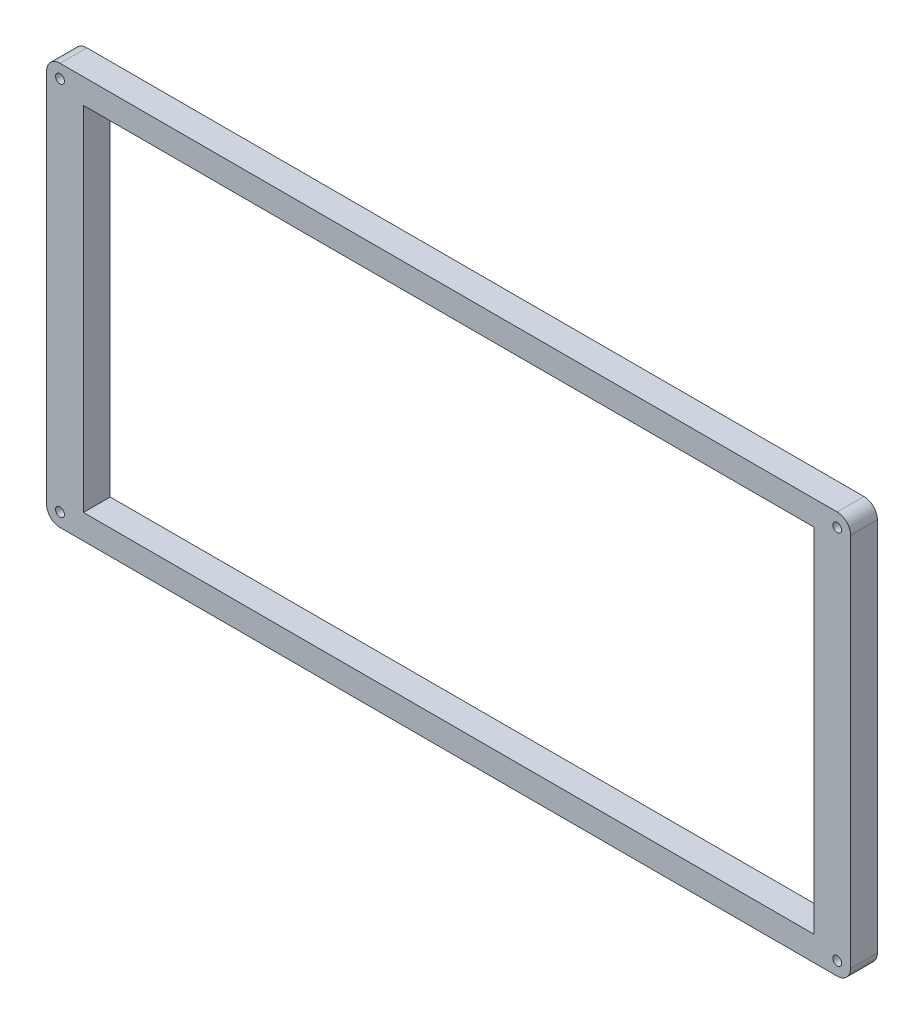
SolidWorks part; units mm, degrees
ref_plane "前视基准面" through (0, 0, 0) normal (0, 0, 1) x (1, 0, 0)
ref_plane "上视基准面" through (0, 0, 0) normal (0, 1, 0) x (1, 0, 0)
ref_plane "右视基准面" through (0, 0, 0) normal (1, 0, 0) x (0, 0, -1)
sketch "草图1" plane through (0, 0, 0) normal (0, 0, 1) x (1, 0, 0)
  line L1 (-77.1552, 109.8741) -> (212.8448, 109.8741)
  line L2 (-82.1552, 104.8741) -> (-82.1552, -35.1259)
  line L3 (-77.1552, -40.1259) -> (212.8448, -40.1259)
  line L4 (217.8448, 104.8741) -> (217.8448, -35.1259)
  line L7 (-68.4171, -30.9075) -> (204.1067, -30.9075)
  line L8 (-68.4171, -30.9075) -> (-68.4171, 100.6557)
  line L9 (-68.4171, 100.6557) -> (204.1067, 100.6557)
  line L10 (204.1067, -30.9075) -> (204.1067, 100.6557)
  arc A0 (212.8448, 109.8741) -> (217.8448, 104.8741) centre (212.8448, 104.8741) cw
  arc A1 (-77.1552, 109.8741) -> (-82.1552, 104.8741) centre (-77.1552, 104.8741) ccw
  arc A2 (-82.1552, -35.1259) -> (-77.1552, -40.1259) centre (-77.1552, -35.1259) ccw
  arc A3 (212.8448, -40.1259) -> (217.8448, -35.1259) centre (212.8448, -35.1259) ccw
  circle A4 centre (-77.1552, 104.8741) radius 1.65
  circle A5 centre (212.8448, -35.1259) radius 1.65
  circle A6 centre (-77.1552, -35.1259) radius 1.65
  circle A7 centre (212.8448, 104.8741) radius 1.65
  point P8 (-82.1552, 109.8741)
  point P11 (-82.1552, -40.1259)
  point P14 (217.8448, -40.1259)
  point P19 (67.8448, 34.8741)
  point P24 (0, 0)
  dimension "D1" = 5
  dimension "D4" = 5
  dimension "D5" = 5
  dimension "D6" = 5
  dimension "D2" = 300
  dimension "D3" = 150
extrude "凸台-拉伸4" add sketch "草图1" along normal blind 10
